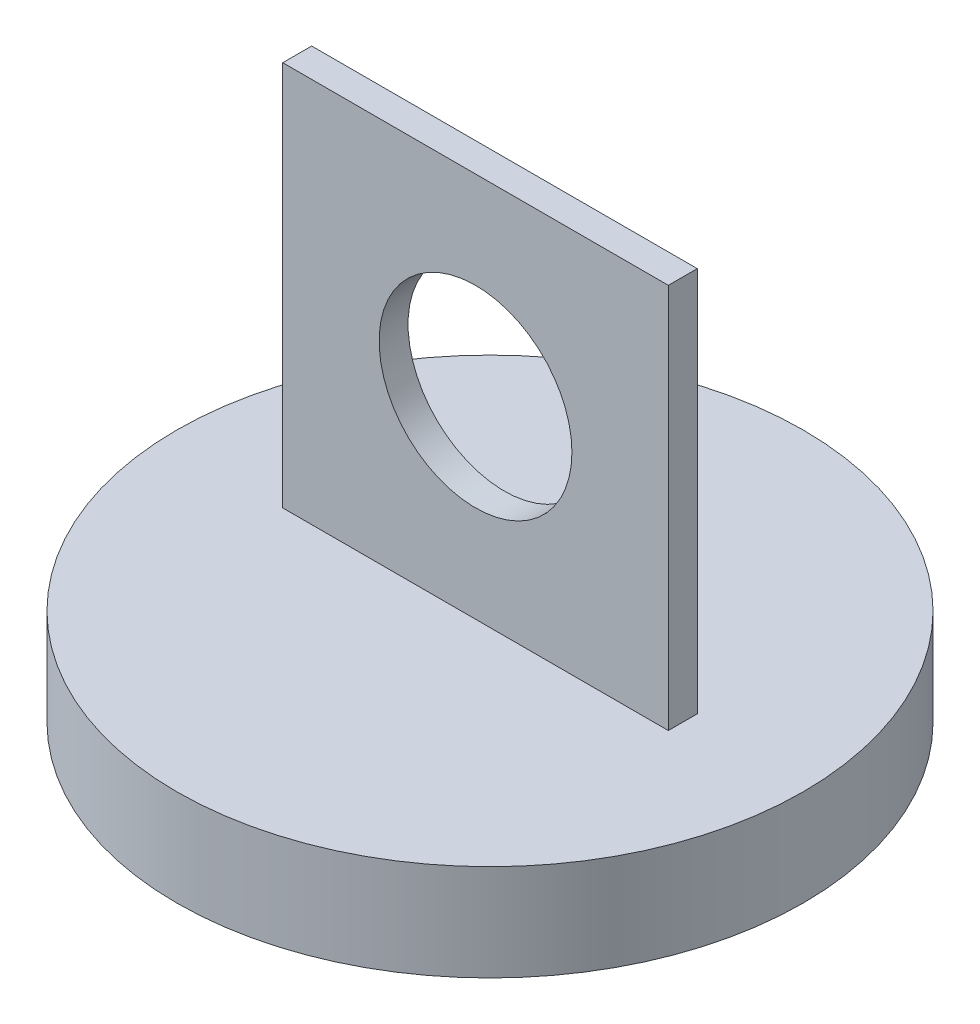
SolidWorks part; units mm, degrees
ref_plane "Front Plane" through (0, 0, 0) normal (0, 0, 1) x (1, 0, 0)
ref_plane "Top Plane" through (0, 0, 0) normal (0, 1, 0) x (1, 0, 0)
ref_plane "Right Plane" through (0, 0, 0) normal (1, 0, 0) x (0, 0, -1)
sketch "Sketch1" plane through (0, 0, 0) normal (0, 1, 0) x (1, 0, 0)
  line L2 (-32.5, 0) -> (75, 0) construction
  circle A1 centre (0, 0) radius 32.5
  dimension "D2" = 65
extrude "Boss-Extrude1" add sketch "Sketch1" along normal blind 10
sketch "Sketch4" plane through (0, 10, 0) normal (0, 1, 0) x (1, 0, 0)
  line L0 (20, 1.5) -> (-20, 1.5)
  line L1 (20, 1.5) -> (20, -1.5)
  line L2 (20, -1.5) -> (-20, -1.5)
  line L3 (-20, 1.5) -> (-20, -1.5)
  line L4 (20, 1.5) -> (-20, -1.5) construction
  line L5 (20, -1.5) -> (-20, 1.5) construction
  point P0 (0, 0)
  dimension "D1" = 3
  dimension "D2" = 40
extrude "Boss-Extrude3" add sketch "Sketch4" along normal blind 40
sketch "Sketch5" plane through (0, 0, 1.5) normal (0, 0, 1) x (1, 0, 0)
  line L0 (-20, 50) -> (20, 50) construction
  line L1 (20, 50) -> (20, 10) construction
  circle A0 centre (0, 30) radius 10
  point P5 (0, 50)
  point P8 (20, 30)
  dimension "D1" = 20
extrude "Cut-Extrude2" cut sketch "Sketch5" against normal blind 40
